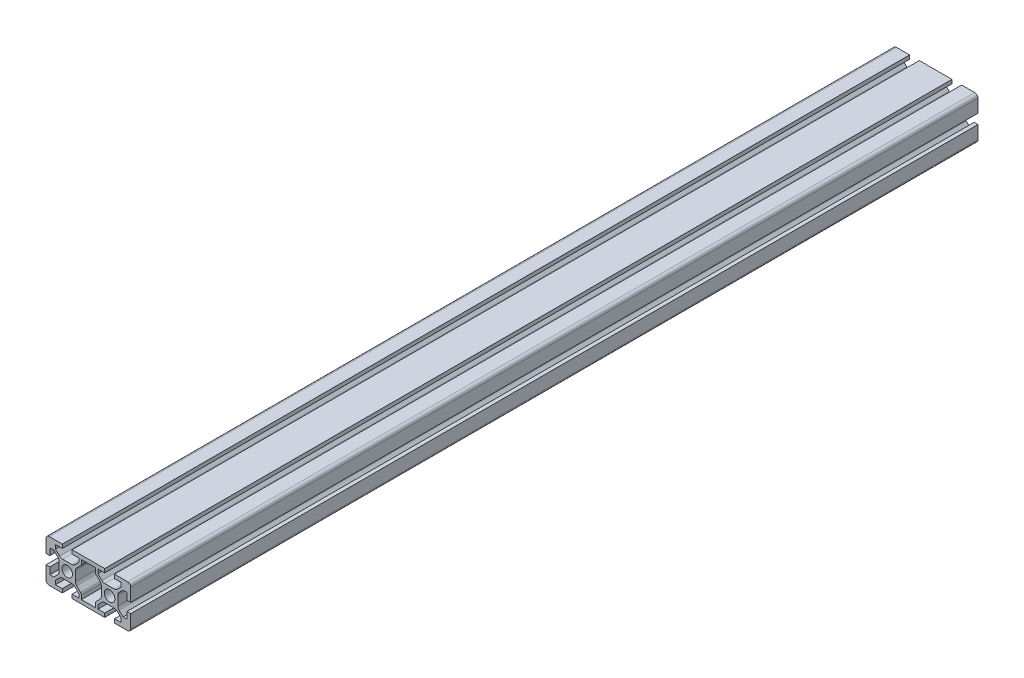
SolidWorks part; units mm, degrees
ref_plane "Alzado" through (0, 0, 0) normal (0, 0, 1) x (1, 0, 0)
ref_plane "Planta" through (0, 0, 0) normal (0, 1, 0) x (1, 0, 0)
ref_plane "Vista lateral" through (0, 0, 0) normal (1, 0, 0) x (0, 0, -1)
sketch "Croquis1" plane through (0, 0, 0) normal (0, 0, 1) x (1, 0, 0)
  line L0 (0, 0) -> (-10, 0) construction
  line L1 (-10, 0) -> (-10, 10) construction
  line L2 (-10, 10) -> (0, 10) construction
  line L3 (0, 10) -> (0, 0) construction
  line L4 (-10, 8.5) -> (-10, 2.3)
  line L5 (-8.2, 2.3) -> (-8.2, 5.5)
  line L6 (-6.3485, 5.5) -> (-4.4858, 3.6373)
  line L7 (-10, 10) -> (0, 0) construction
  line L8 (-3.9, 2.223) -> (-3.9, 0)
  line L9 (-8.2, 5.5) -> (-6.3485, 5.5)
  line L14 (-10, 2.3) -> (-8.2, 2.3)
  line L15 (-2.223, 3.9) -> (0, 3.9)
  line L16 (-5.5, 6.3485) -> (-3.6373, 4.4858)
  line L17 (-5.5, 8.2) -> (-5.5, 6.3485)
  line L18 (-2.3, 10) -> (-2.3, 8.2)
  line L19 (-2.3, 8.2) -> (-5.5, 8.2)
  line L20 (-8.5, 10) -> (-2.3, 10)
  line L22 (2.3, 10) -> (2.3, 8.2)
  line L23 (2.3, 8.2) -> (5.5, 8.2)
  line L24 (5.5, 8.2) -> (5.5, 6.3485)
  line L25 (5.5, 6.3485) -> (3.6373, 4.4858)
  line L26 (2.223, 3.9) -> (0, 3.9)
  line L27 (3.9, 2.223) -> (3.9, 0)
  line L37 (6.3339, -5.4854) -> (4.4858, -3.6373)
  line L38 (3.9, -2.223) -> (3.9, 0)
  line L39 (2.223, -3.9) -> (0, -3.9)
  line L40 (5.5, -6.3485) -> (3.6373, -4.4858)
  line L41 (5.5, -8.2) -> (5.5, -6.3485)
  line L42 (2.3, -8.2) -> (5.5, -8.2)
  line L43 (2.3, -10) -> (2.3, -8.2)
  line L45 (-8.5, -10) -> (-2.3, -10)
  line L46 (-2.3, -10) -> (-2.3, -8.2)
  line L47 (-2.3, -8.2) -> (-5.5, -8.2)
  line L48 (-5.5, -8.2) -> (-5.5, -6.3485)
  line L49 (-5.5, -6.3485) -> (-3.6373, -4.4858)
  line L50 (-2.223, -3.9) -> (0, -3.9)
  line L51 (-3.9, -2.223) -> (-3.9, 0)
  line L52 (-6.3485, -5.5) -> (-4.4858, -3.6373)
  line L53 (-8.2, -5.5) -> (-6.3485, -5.5)
  line L54 (-8.2, -2.3) -> (-8.2, -5.5)
  line L55 (-10, -2.3) -> (-8.2, -2.3)
  line L56 (-10, -8.5) -> (-10, -2.3)
  line L60 (16.1, 2.223) -> (16.1, 0)
  line L63 (17.777, 3.9) -> (20, 3.9)
  line L64 (14.5, 6.3485) -> (16.3627, 4.4858)
  line L65 (14.5, 8.2) -> (14.5, 6.3485)
  line L66 (17.7, 10) -> (17.7, 8.2)
  line L67 (17.7, 8.2) -> (14.5, 8.2)
  line L69 (28.5, 10) -> (22.3, 10)
  line L70 (22.3, 10) -> (22.3, 8.2)
  line L71 (22.3, 8.2) -> (25.5, 8.2)
  line L72 (25.5, 8.2) -> (25.5, 6.3485)
  line L73 (25.5, 6.3485) -> (23.6373, 4.4858)
  line L74 (22.223, 3.9) -> (20, 3.9)
  line L75 (23.9, 2.223) -> (23.9, 0)
  line L76 (26.3485, 5.5) -> (24.4858, 3.6373)
  line L77 (28.2, 5.5) -> (26.3485, 5.5)
  line L78 (28.2, 2.3) -> (28.2, 5.5)
  line L79 (30, 2.3) -> (28.2, 2.3)
  line L80 (30, 8.5) -> (30, 2.3)
  line L81 (30, -8.5) -> (30, -2.3)
  line L82 (30, -2.3) -> (28.2, -2.3)
  line L83 (28.2, -2.3) -> (28.2, -5.5)
  line L84 (28.2, -5.5) -> (26.3485, -5.5)
  line L85 (26.3485, -5.5) -> (24.4858, -3.6373)
  line L86 (23.9, -2.223) -> (23.9, 0)
  line L87 (22.223, -3.9) -> (20, -3.9)
  line L88 (25.5, -6.3485) -> (23.6373, -4.4858)
  line L89 (25.5, -8.2) -> (25.5, -6.3485)
  line L90 (22.3, -8.2) -> (25.5, -8.2)
  line L91 (22.3, -10) -> (22.3, -8.2)
  line L92 (28.5, -10) -> (22.3, -10)
  line L94 (17.7, -10) -> (17.7, -8.2)
  line L95 (17.7, -8.2) -> (14.5, -8.2)
  line L96 (14.5, -8.2) -> (14.5, -6.3485)
  line L97 (14.5, -6.3485) -> (16.3627, -4.4858)
  line L98 (17.777, -3.9) -> (20, -3.9)
  line L99 (16.1, -2.223) -> (16.1, 0)
  line L100 (13.6661, -5.4854) -> (15.5142, -3.6373)
  line L105 (2.3, -10) -> (17.7, -10)
  line L106 (6.7, -6.3692) -> (6.7, -8.2)
  line L107 (10, -8.5) -> (10, -2.3) [skipped]
  line L108 (10, -2.3) -> (8.2, -2.3) [skipped]
  line L109 (8.2, -2.3) -> (8.2, -5.5) [skipped]
  line L110 (8.2, -5.5) -> (6.3485, -5.5) [skipped]
  line L111 (8.5, -10) -> (2.3, -10) [skipped]
  line L112 (11.5, -10) -> (17.7, -10) [skipped]
  line L113 (11.8, -5.5) -> (13.6515, -5.5) [skipped]
  line L114 (11.8, -2.3) -> (11.8, -5.5) [skipped]
  line L115 (10, -2.3) -> (11.8, -2.3) [skipped]
  line L116 (10, -8.5) -> (10, -2.3) [skipped]
  line L117 (13.3, -6.3692) -> (13.3, -8.2)
  line L118 (6.7, -8.2) -> (13.3, -8.2)
  line L120 (8.5, 10) -> (2.3, 10) [skipped]
  line L121 (6.3485, 5.5) -> (4.4858, 3.6373) [skipped]
  line L122 (8.2, 5.5) -> (6.3485, 5.5) [skipped]
  line L123 (8.2, 2.3) -> (8.2, 5.5) [skipped]
  line L124 (10, 2.3) -> (8.2, 2.3) [skipped]
  line L125 (10, 8.5) -> (10, 2.3) [skipped]
  line L126 (10, 8.5) -> (10, 2.3) [skipped]
  line L127 (11.8, 2.3) -> (11.8, 5.5) [skipped]
  line L128 (13.6515, 5.5) -> (15.5142, 3.6373) [skipped]
  line L129 (11.8, 5.5) -> (13.6515, 5.5) [skipped]
  line L130 (10, 2.3) -> (11.8, 2.3) [skipped]
  line L131 (11.5, 10) -> (17.7, 10) [skipped]
  line L132 (13.6661, 5.4854) -> (15.5142, 3.6373)
  line L133 (13.3, 6.3692) -> (13.3, 8.2)
  line L134 (6.7, 8.2) -> (13.3, 8.2)
  line L135 (6.7, 6.3692) -> (6.7, 8.2)
  line L136 (2.3, 10) -> (17.7, 10)
  line L137 (6.3339, 5.4854) -> (4.4858, 3.6373)
  arc A0 (-8.5, 10) -> (-10, 8.5) centre (-8.5, 8.5) ccw
  arc A1 (0, 2.5) -> (-2.5, 0) centre (0, 0) ccw
  arc A2 (-3.9, 2.223) -> (-4.4858, 3.6373) centre (-5.9, 2.223) ccw
  arc A3 (-2.223, 3.9) -> (-3.6373, 4.4858) centre (-2.223, 5.9) cw
  arc A4 (2.223, 3.9) -> (3.6373, 4.4858) centre (2.223, 5.9) ccw
  arc A5 (2.5, 0) -> (0, 2.5) centre (0, 0) ccw
  arc A6 (3.9, 2.223) -> (4.4858, 3.6373) centre (5.9, 2.223) cw
  arc A8 (3.9, -2.223) -> (4.4858, -3.6373) centre (5.9, -2.223) ccw
  arc A9 (0, -2.5) -> (2.5, 0) centre (0, 0) ccw
  arc A10 (2.223, -3.9) -> (3.6373, -4.4858) centre (2.223, -5.9) cw
  arc A12 (-2.223, -3.9) -> (-3.6373, -4.4858) centre (-2.223, -5.9) ccw
  arc A13 (-2.5, 0) -> (0, -2.5) centre (0, 0) ccw
  arc A14 (-3.9, -2.223) -> (-4.4858, -3.6373) centre (-5.9, -2.223) cw
  arc A15 (-10, -8.5) -> (-8.5, -10) centre (-8.5, -8.5) ccw
  arc A17 (20, 2.5) -> (17.5, 0) centre (20, 0) ccw
  arc A18 (16.1, 2.223) -> (15.5142, 3.6373) centre (14.1, 2.223) ccw
  arc A19 (17.777, 3.9) -> (16.3627, 4.4858) centre (17.777, 5.9) cw
  arc A20 (22.223, 3.9) -> (23.6373, 4.4858) centre (22.223, 5.9) ccw
  arc A21 (22.5, 0) -> (20, 2.5) centre (20, 0) ccw
  arc A22 (23.9, 2.223) -> (24.4858, 3.6373) centre (25.9, 2.223) cw
  arc A23 (30, 8.5) -> (28.5, 10) centre (28.5, 8.5) ccw
  arc A24 (23.9, -2.223) -> (24.4858, -3.6373) centre (25.9, -2.223) ccw
  arc A25 (20, -2.5) -> (22.5, 0) centre (20, 0) ccw
  arc A26 (22.223, -3.9) -> (23.6373, -4.4858) centre (22.223, -5.9) cw
  arc A27 (28.5, -10) -> (30, -8.5) centre (28.5, -8.5) ccw
  arc A28 (17.777, -3.9) -> (16.3627, -4.4858) centre (17.777, -5.9) ccw
  arc A29 (17.5, 0) -> (20, -2.5) centre (20, 0) ccw
  arc A30 (16.1, -2.223) -> (15.5142, -3.6373) centre (14.1, -2.223) cw
  arc A32 (10, 8.5) -> (8.5, 10) centre (8.5, 8.5) ccw [skipped]
  arc A33 (11.5, 10) -> (10, 8.5) centre (11.5, 8.5) ccw [skipped]
  arc A34 (8.5, -10) -> (10, -8.5) centre (8.5, -8.5) ccw [skipped]
  arc A35 (10, -8.5) -> (11.5, -10) centre (11.5, -8.5) ccw [skipped]
  arc A38 (6.7, -6.3692) -> (6.3339, -5.4854) centre (5.45, -6.3692) ccw
  arc A39 (13.6661, -5.4854) -> (13.3, -6.3692) centre (14.55, -6.3692) ccw
  arc A40 (13.6661, 5.4854) -> (13.3, 6.3692) centre (14.55, 6.3692) cw
  arc A41 (6.7, 6.3692) -> (6.3339, 5.4854) centre (5.45, 6.3692) cw
  point P92 (0, 0)
  point P161 (20, 0)
  dimension "D3" = 3
  dimension "D9" = 2.5
  dimension "D10" = 2
  dimension "D15" = 2.5
  dimension "D16" = 2.5
  dimension "D2" = 10
  dimension "D4" = 6.2
  dimension "D5" = 1.8
  dimension "D6" = 0.6
  dimension "D7" = 6.1
  dimension "D8" = 5.5
  dimension "D13" = 1.2
  dimension "D14" = 1.2
  dimension "D12" = 2
  dimension "D11" = 4
extrude "Saliente-Extruir1" add sketch "Croquis1" along normal mid plane 400
